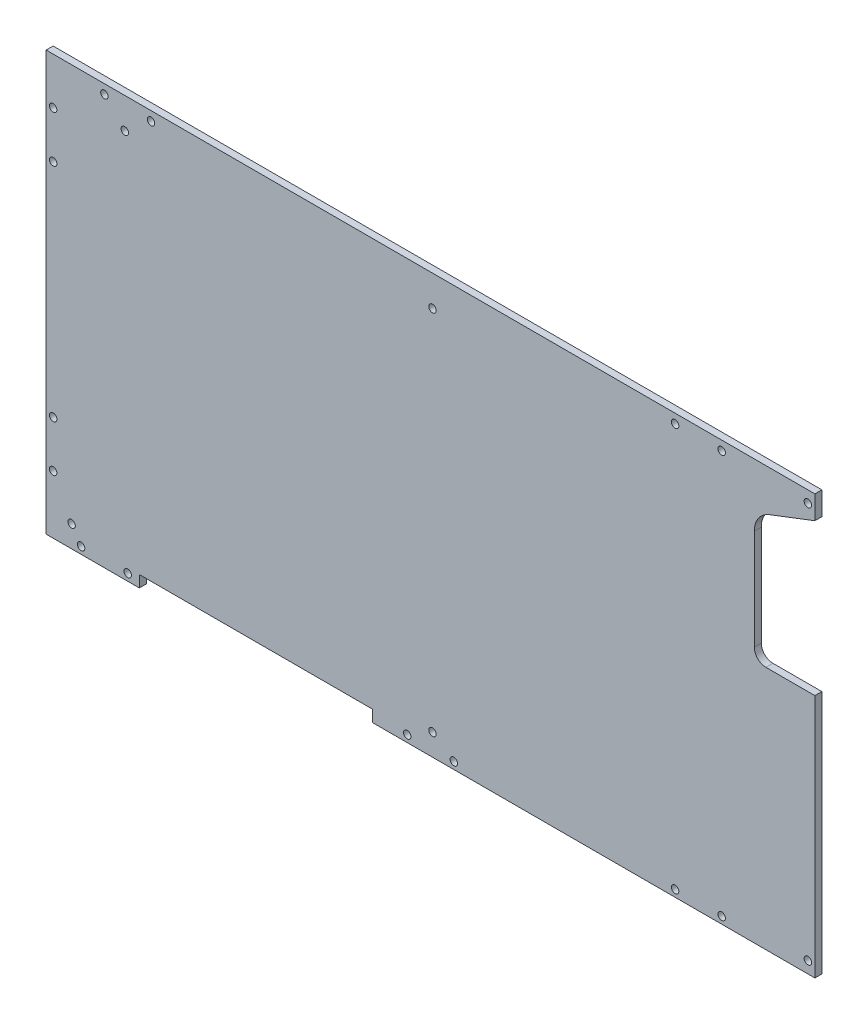
SolidWorks part; units mm, degrees
ref_plane "前视基准面" through (0, 0, 0) normal (0, 0, 1) x (1, 0, 0)
ref_plane "上视基准面" through (0, 0, 0) normal (0, 1, 0) x (1, 0, 0)
ref_plane "右视基准面" through (0, 0, 0) normal (1, 0, 0) x (0, 0, -1)
sketch "草图1" plane through (0, 0, 0) normal (0, 0, 1) x (1, 0, 0)
  line L1 (0, 0) -> (330, 0)
  line L2 (0, 0) -> (0, 180)
  line L3 (0, 180) -> (330, 180)
  line L4 (330, 0) -> (330, 180)
  dimension "D1" = 330
  dimension "D2" = 180
extrude "凸台-拉伸1" add sketch "草图1" along normal blind 3
sketch "草图2" plane through (0, 0, 3) normal (0, 0, 1) x (1, 0, 0)
  line L0 (10.91, 9.35) -> (165.85, 9.35) construction
  line L1 (165.85, 9.35) -> (165.85, 166.83) construction
  line L2 (165.85, 166.83) -> (33.77, 166.83) construction
  line L3 (33.77, 166.83) -> (10.91, 9.35) construction
  line L4 (0, 0) -> (330, 0) construction
  circle A0 centre (33.77, 166.83) radius 1.6
  circle A1 centre (165.85, 166.83) radius 1.6
  circle A2 centre (10.91, 9.35) radius 1.6
  circle A3 centre (165.85, 9.35) radius 1.6
  dimension "D6" = 3.2
  dimension "D1" = 9.35
  dimension "D2" = 10.91
  dimension "D3" = 154.94
  dimension "D4" = 157.48
  dimension "D5" = 132.08
extrude "切除-拉伸1" cut sketch "草图2" against normal through all
sketch "草图3" plane through (0, 0, 3) normal (0, 0, 1) x (1, 0, 0)
  line L0 (3, 25) -> (3, 45) construction
  line L1 (3, 160) -> (3, 140) construction
  line L2 (0, 180) -> (0, 0) construction
  line L3 (0, 0) -> (330, 0) construction
  line L4 (330, 180) -> (0, 180) construction
  line L5 (15, 3) -> (35, 3) construction
  line L6 (155, 3) -> (175, 3) construction
  line L8 (25, 176) -> (45, 176) construction
  line L9 (270, 176) -> (290, 176) construction
  line L10 (330, 0) -> (330, 180) construction
  line L11 (270, 3) -> (290, 3) construction
  circle A0 centre (3, 160) radius 1.6
  circle A1 centre (3, 140) radius 1.6
  circle A2 centre (3, 45) radius 1.6
  circle A3 centre (3, 25) radius 1.6
  circle A4 centre (15, 3) radius 1.6
  circle A5 centre (35, 3) radius 1.6
  circle A6 centre (155, 3) radius 1.6
  circle A7 centre (175, 3) radius 1.6
  circle A8 centre (25, 176) radius 1.6
  circle A9 centre (45, 176) radius 1.6
  circle A10 centre (270, 176) radius 1.6
  circle A11 centre (290, 176) radius 1.6
  circle A12 centre (270, 3) radius 1.6
  circle A13 centre (290, 3) radius 1.6
  circle A14 centre (327, 5) radius 1.6
  circle A15 centre (327, 175) radius 1.6
  dimension "D5" = 3.2
  dimension "D1" = 20
  dimension "D2" = 3
  dimension "D3" = 25
  dimension "D4" = 20
  dimension "D6" = 3
  dimension "D7" = 15
  dimension "D8" = 120
  dimension "D9" = 4
  dimension "D10" = 25
  dimension "D11" = 40
  dimension "D12" = 40
  dimension "D13" = 3
  dimension "D14" = 5
  dimension "D15" = 3
  dimension "D16" = 5
extrude "切除-拉伸2" cut sketch "草图3" against normal through all
sketch "草图4" plane through (0, 0, 3) normal (0, 0, 1) x (1, 0, 0)
  line L0 (0, 0) -> (330, 0) construction
  line L1 (40, 0) -> (140, 0)
  line L2 (40, 0) -> (40, 5)
  line L3 (40, 5) -> (140, 5)
  line L4 (140, 0) -> (140, 5)
  line L5 (0, 180) -> (0, 0) construction
  dimension "D1" = 5
  dimension "D2" = 40
  dimension "D3" = 100
extrude "切除-拉伸3" cut sketch "草图4" against normal up to next
sketch "草图6" plane through (0, 0, 3) normal (0, 0, 1) x (1, 0, 0)
  line L0 (330, 0) -> (330, 180) construction
  line L2 (330, 170) -> (330, 105)
  line L3 (330, 105) -> (309, 105)
  line L4 (304, 153.132) -> (304, 110)
  line L5 (330, 180) -> (0, 180) construction
  line L6 (310.4102, 162.4655) -> (330, 170)
  arc A0 (309, 105) -> (304, 110) centre (309, 110) cw
  arc A2 (304, 153.132) -> (310.4102, 162.4655) centre (314, 153.132) cw
  point P12 (305, 170)
  point P13 (304, 160)
  dimension "D4" = 5
  dimension "D7" = 10
  dimension "D1" = 25
  dimension "D2" = 10
  dimension "D3" = 75
  dimension "D5" = 20
  dimension "D6" = 26
extrude "切除-拉伸4" cut sketch "草图6" against normal up to next
